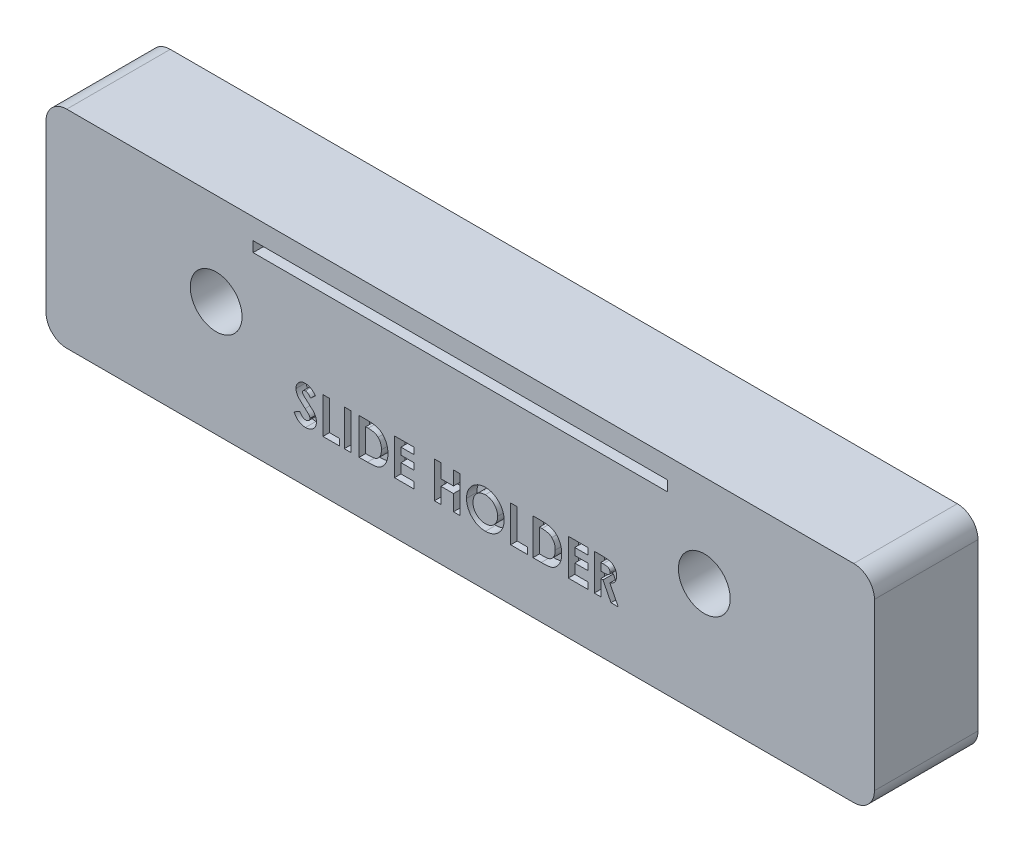
SolidWorks part; units mm, degrees
ref_plane "Front Plane" through (0, 0, 0) normal (0, 0, 1) x (1, 0, 0)
ref_plane "Top Plane" through (0, 0, 0) normal (0, 1, 0) x (1, 0, 0)
ref_plane "Right Plane" through (0, 0, 0) normal (1, 0, 0) x (0, 0, -1)
sketch "Sketch1" plane through (0, 0, 0) normal (0, 0, 1) x (1, 0, 0)
  line L1 (-40.3722, 21.485) -> (39.6278, 21.485)
  line L2 (-40.3722, 21.485) -> (-40.3722, 1.485)
  line L3 (-40.3722, 1.485) -> (39.6278, 1.485)
  line L4 (39.6278, 21.485) -> (39.6278, 1.485)
  dimension "D1" = 80
  dimension "D2" = 20
extrude "Boss-Extrude1" add sketch "Sketch1" along normal blind 10
sketch "Sketch2" plane through (0, 0, 10) normal (0, 0, 1) x (1, 0, 0)
  line L0 (39.6278, 21.485) -> (-40.3722, 21.485) construction
  line L1 (-40.3722, 21.485) -> (-40.3722, 1.485) construction
  line L2 (-0.3722, 21.485) -> (-0.3722, 1.485) construction
  line L3 (-40.3722, 1.485) -> (39.6278, 1.485) construction
  circle A0 centre (-23.9422, 12.585) radius 2.5
  circle A1 centre (23.1978, 12.585) radius 2.5
  dimension "D1" = 5
  dimension "D2" = 8.9
  dimension "D3" = 16.43
extrude "Cut-Extrude1" cut sketch "Sketch2" against normal blind 10
sketch "Sketch3" plane through (0, 0, 10) normal (0, 0, 1) x (1, 0, 0)
  line L0 (39.6278, 21.485) -> (-40.3722, 21.485) construction
  line L1 (-20.3722, 19.485) -> (19.6278, 19.485)
  line L2 (-20.3722, 19.485) -> (-20.3722, 18.485)
  line L3 (-20.3722, 18.485) -> (19.6278, 18.485)
  line L4 (19.6278, 19.485) -> (19.6278, 18.485)
  point P6 (-0.3722, 19.485)
  point P7 (-0.3722, 21.485)
  dimension "D1" = 1
  dimension "D2" = 2
  dimension "D3" = 40
extrude "Cut-Extrude2" cut sketch "Sketch3" against normal through all
sketch "Sketch4" plane through (0, 0, 10) normal (0, 0, 1) x (1, 0, 0)
  line L0 (-40.3722, 6.485) -> (39.6278, 6.485) construction
  line L1 (-40.3722, 21.485) -> (-40.3722, 1.485) construction
  line L3 (-40.3722, 1.485) -> (39.6278, 1.485) construction
  line L4 (39.6278, 1.485) -> (39.6278, 21.485) construction
  text T0 "<b>SLIDE HOLDER</b>"
  dimension "D1" = 5
extrude "Cut-Extrude3" cut sketch "Sketch4" against normal blind 1
fillet "Fillet1" radius 2 4 edges at (39.6278, 21.485, 5) (39.6278, 1.485, 5) (-40.3722, 1.485, 5) (-40.3722, 21.485, 5)
